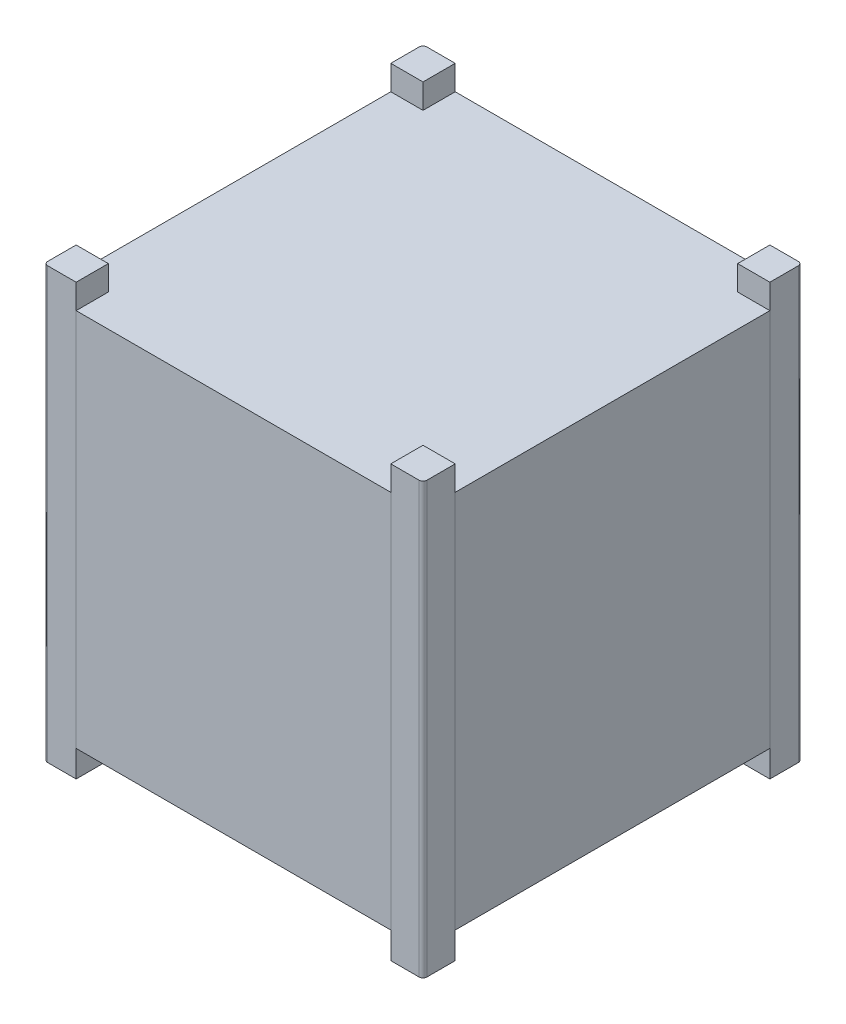
SolidWorks part; units mm, degrees
ref_plane "Front Plane" through (0, 0, 0) normal (0, 0, 1) x (1, 0, 0)
ref_plane "Top Plane" through (0, 0, 0) normal (0, 1, 0) x (1, 0, 0)
ref_plane "Right Plane" through (0, 0, 0) normal (1, 0, 0) x (0, 0, -1)
sketch "Sketch1" plane through (0, 0, 0) normal (0, 1, 0) x (1, 0, 0)
  line L1 (-50, -50) -> (50, -50)
  line L2 (-50, -50) -> (-50, 50)
  line L3 (-50, 50) -> (50, 50)
  line L4 (50, -50) -> (50, 50)
  line L5 (-50, -50) -> (50, 50) construction
  line L6 (-50, 50) -> (50, -50) construction
  point P0 (0, 0)
  dimension "D1" = 100
extrude "Boss-Extrude1" add sketch "Sketch1" along normal mid plane 100
sketch "Sketch2" plane through (0, 0, 50) normal (0, 0, -1) x (1, 0, 0)
  line L1 (-50, 57) -> (-41.5, 57)
  line L2 (-50, 57) -> (-50, -56.5)
  line L3 (-50, -56.5) -> (-41.5, -56.5)
  line L4 (-41.5, 57) -> (-41.5, -56.5)
  line L5 (41.5, -56.5) -> (50, -56.5)
  line L6 (41.5, -56.5) -> (41.5, 57)
  line L7 (41.5, 57) -> (50, 57)
  line L8 (50, -56.5) -> (50, 57)
  line L12 (-50, -50) -> (-50, 50) construction
  line L13 (50, -50) -> (50, 50) construction
  line L14 (-50, -50) -> (50, -50) construction
  dimension "D1" = 113.5
  dimension "D2" = 6.5
  dimension "D3" = 8.5
extrude "Boss-Extrude2" add sketch "Sketch2" along normal blind 8.5
mirror "Mirror1" about plane through (0, 0, 0) normal (0, 0, 1) of "Boss-Extrude2"
sketch "Sketch4" plane through (0, 0, 50) normal (0, 0, 1) x (1, 0, 0)
  line L1 (-41.5, 56.5) -> (-50, 56.5)
  line L2 (-41.5, 56.5) -> (-41.5, -57)
  line L3 (-41.5, -57) -> (-50, -57)
  line L4 (-50, 56.5) -> (-50, -57)
  line L5 (41.5, -57) -> (50, -57)
  line L6 (41.5, -57) -> (41.5, 56.5)
  line L7 (41.5, 56.5) -> (50, 56.5)
  line L8 (50, -57) -> (50, 56.5)
split line "Split Line1"
sketch "Sketch5" plane through (-50, 0, 0) normal (-1, 0, 0) x (0, 0, 1)
  line L1 (-50, -57) -> (-41.5, -57)
  line L2 (-50, -57) -> (-50, 56.5)
  line L3 (-50, 56.5) -> (-41.5, 56.5)
  line L4 (-41.5, -57) -> (-41.5, 56.5)
  line L5 (41.5, 56.5) -> (50, 56.5)
  line L6 (41.5, 56.5) -> (41.5, -57)
  line L7 (41.5, -57) -> (50, -57)
  line L8 (50, 56.5) -> (50, -57)
split line "Split Line2"
fillet "Fillet1" radius 1
